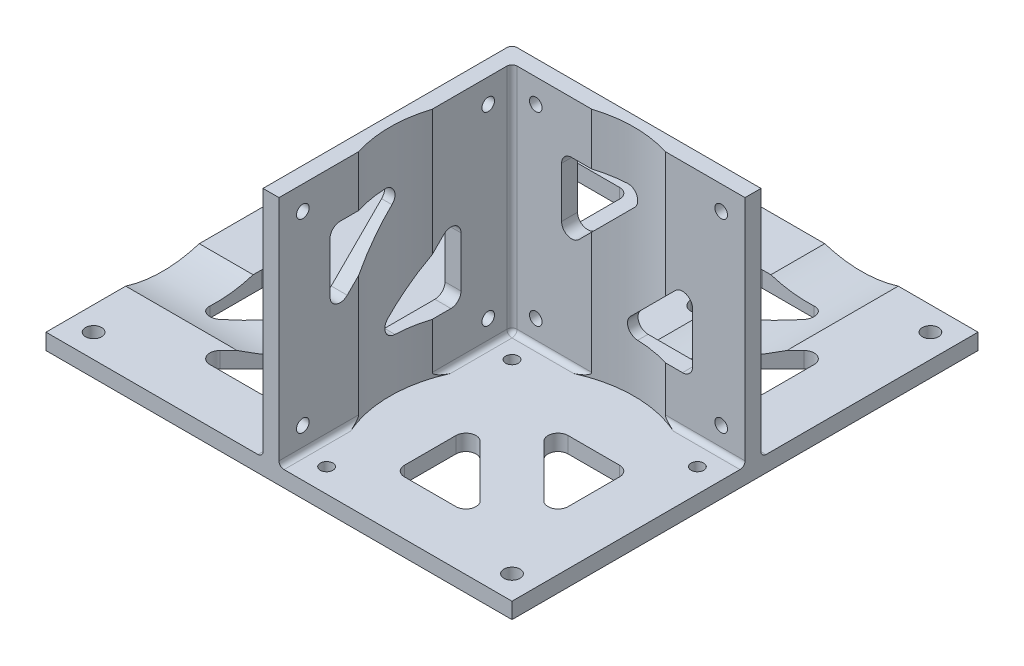
SolidWorks part; units mm, degrees
ref_plane "Front Plane" through (0, 0, 0) normal (0, 0, 1) x (1, 0, 0)
ref_plane "Top Plane" through (0, 0, 0) normal (0, 1, 0) x (1, 0, 0)
ref_plane "Right Plane" through (0, 0, 0) normal (1, 0, 0) x (0, 0, -1)
sketch "Sketch1" plane through (0, 0, 0) normal (0, 1, 0) x (1, 0, 0)
  line L0 (-41.525, 46.25) -> (-41.525, -46.25) construction
  line L1 (-46.25, -46.25) -> (46.25, -46.25)
  line L2 (-46.25, -46.25) -> (-46.25, 46.25)
  line L3 (-46.25, 46.25) -> (46.25, 46.25)
  line L4 (46.25, -46.25) -> (46.25, 46.25)
  line L5 (-46.25, -46.25) -> (46.25, 46.25) construction
  line L6 (-46.25, 46.25) -> (46.25, -46.25) construction
  line L7 (-46.25, -41.525) -> (46.25, -41.525) construction
  line L8 (41.525, -46.25) -> (41.525, 46.25) construction
  line L9 (-46.25, 41.525) -> (46.25, 41.525) construction
  circle A0 centre (-41.525, -41.525) radius 1.6
  circle A1 centre (-41.525, 41.525) radius 1.6
  circle A2 centre (41.525, 41.525) radius 1.6
  circle A3 centre (41.525, -41.525) radius 1.6
  point P0 (0, 0)
  dimension "D7" = 3.2
  dimension "D8" = 3.2
  dimension "D9" = 3.2
  dimension "D10" = 3.2
  dimension "D1" = 92.5
  dimension "D2" = 92.5
  dimension "D3" = 4.725
  dimension "D4" = 4.725
  dimension "D5" = 4.725
  dimension "D6" = 4.725
extrude "Base Plate" add sketch "Sketch1" along normal blind 3.175
sketch "Sketch2" plane through (0, 3.175, 0) normal (0, 1, 0) x (1, 0, 0)
  line L0 (0, 0) -> (46.25, 0)
  line L1 (46.25, -46.25) -> (46.25, 46.25) construction
  line L2 (0, 0) -> (0, -46.25)
  line L3 (-46.25, -46.25) -> (46.25, -46.25) construction
  line L4 (-3.175, -46.25) -> (-3.175, 3.175)
  line L7 (-3.175, 3.175) -> (46.25, 3.175)
  line L8 (-3.175, -46.25) -> (0, -46.25)
  line L9 (46.25, 0) -> (46.25, 3.175)
  dimension "D1" = 46.25
  dimension "D2" = 3.175
  dimension "D3" = 3.175
extrude "L-Bracket" add sketch "Sketch2" along normal blind 46.25
sketch "Sketch3" plane through (0, 3.175, 0) normal (0, 1, 0) x (1, 0, 0)
  line L0 (0, 0) -> (46.25, -46.25) construction
  line L1 (0, -46.25) -> (46.25, 0) construction
  line L5 (0, -46.25) -> (0, 0) construction
  circle A0 centre (23.125, -23.125) radius 21.625 construction
  circle A2 centre (41.525, -4.725) radius 0.2
  circle A3 centre (4.725, -4.725) radius 0.2
  circle A4 centre (4.725, -41.525) radius 0.2
  dimension "D1" = 43.25
  dimension "D4" = 4.725
extrude "RW Holes" cut sketch "Sketch3" against normal through all
sketch "Sketch7" plane through (0, 0, 0) normal (0, 0, 1) x (1, 0, 0)
  line L0 (0, 3.175) -> (46.25, 49.425) construction
  line L1 (0, 49.425) -> (46.25, 3.175) construction
  line L2 (46.25, 49.425) -> (46.25, 3.175) construction
  line L3 (0, 3.175) -> (46.25, 3.175) construction
  circle A0 centre (23.125, 26.3) radius 21.625 construction
  circle A1 centre (41.525, 7.9) radius 0.2
  circle A2 centre (4.725, 7.9) radius 0.2
  circle A3 centre (4.725, 44.7) radius 0.2
  circle A4 centre (41.525, 44.7) radius 0.2
  dimension "D1" = 43.25
  dimension "D2" = 0.4
  dimension "D3" = 4
  dimension "D4" = 4.725
  dimension "D5" = 41.525
  dimension "D6" = 4.725
  dimension "D8" = 46.25
extrude "RW Holes 2" cut sketch "Sketch7" against normal through all
sketch "Sketch8" plane through (0, 0, 0) normal (1, 0, 0) x (0, 0, -1)
  line L0 (-46.25, 49.425) -> (0, 3.175) construction
  line L1 (-46.25, 3.175) -> (0, 49.425) construction
  line L2 (-46.25, 3.175) -> (0, 3.175) construction
  circle A0 centre (-23.125, 26.3) radius 21.625 construction
  circle A1 centre (-41.525, 7.9) radius 0.2
  circle A2 centre (-41.525, 44.7) radius 0.2
  circle A3 centre (-4.725, 44.7) radius 0.2
  circle A4 centre (-4.725, 7.9) radius 0.2
  dimension "D1" = 43.25
  dimension "D4" = 0.4
  dimension "D2" = 4
  dimension "D3" = 4.725
  dimension "D5" = 41.525
  dimension "D6" = 4.725
extrude "RW Holes 3" cut sketch "Sketch8" against normal blind 45
sketch "Sketch10" plane through (0, 0, 0) normal (0, -1, 0) x (1, 0, 0)
  line L0 (-46.25, 46.25) -> (46.25, -46.25) construction
  line L1 (21.9291, 15.6133) -> (32.1447, 25.8289)
  line L2 (-46.25, -46.25) -> (46.25, 46.25) construction
  line L3 (35.559, 24.4147) -> (35.559, 14.1991)
  line L4 (33.559, 12.1991) -> (23.3433, 12.1991)
  line L5 (46.25, 46.25) -> (46.25, -46.25) construction
  line L6 (24.4147, 35.559) -> (14.1991, 35.559)
  line L7 (15.6133, 21.9291) -> (25.8289, 32.1447)
  line L8 (12.1991, 33.559) -> (12.1991, 23.3433)
  line L9 (35.559, -24.4147) -> (35.559, -14.1991)
  line L10 (33.559, -12.1991) -> (23.3433, -12.1991)
  line L11 (21.9291, -15.6133) -> (32.1447, -25.8289)
  line L12 (12.1991, -33.559) -> (12.1991, -23.3433)
  line L13 (15.6133, -21.9291) -> (25.8289, -32.1447)
  line L14 (24.4147, -35.559) -> (14.1991, -35.559)
  line L15 (-24.4147, -35.559) -> (-14.1991, -35.559)
  line L16 (-12.1991, -33.559) -> (-12.1991, -23.3433)
  line L17 (-15.6133, -21.9291) -> (-25.8289, -32.1447)
  line L18 (-33.559, -12.1991) -> (-23.3433, -12.1991)
  line L19 (-21.9291, -15.6133) -> (-32.1447, -25.8289)
  line L20 (-35.559, -24.4147) -> (-35.559, -14.1991)
  line L21 (-35.559, 24.4147) -> (-35.559, 14.1991)
  line L22 (-33.559, 12.1991) -> (-23.3433, 12.1991)
  line L23 (-21.9291, 15.6133) -> (-32.1447, 25.8289)
  line L24 (-12.1991, 33.559) -> (-12.1991, 23.3433)
  line L25 (-15.6133, 21.9291) -> (-25.8289, 32.1447)
  line L26 (-24.4147, 35.559) -> (-14.1991, 35.559)
  arc A0 (35.559, 14.1991) -> (33.559, 12.1991) centre (33.559, 14.1991) cw
  arc A1 (32.1447, 25.8289) -> (35.559, 24.4147) centre (33.559, 24.4147) cw
  arc A2 (21.9291, 15.6133) -> (23.3433, 12.1991) centre (23.3433, 14.1991) ccw
  arc A3 (25.8289, 32.1447) -> (24.4147, 35.559) centre (24.4147, 33.559) ccw
  arc A4 (14.1991, 35.559) -> (12.1991, 33.559) centre (14.1991, 33.559) ccw
  arc A5 (15.6133, 21.9291) -> (12.1991, 23.3433) centre (14.1991, 23.3433) cw
  arc A6 (35.559, -14.1991) -> (33.559, -12.1991) centre (33.559, -14.1991) ccw
  arc A7 (21.9291, -15.6133) -> (23.3433, -12.1991) centre (23.3433, -14.1991) cw
  arc A8 (32.1447, -25.8289) -> (35.559, -24.4147) centre (33.559, -24.4147) ccw
  arc A9 (15.6133, -21.9291) -> (12.1991, -23.3433) centre (14.1991, -23.3433) ccw
  arc A10 (14.1991, -35.559) -> (12.1991, -33.559) centre (14.1991, -33.559) cw
  arc A11 (25.8289, -32.1447) -> (24.4147, -35.559) centre (24.4147, -33.559) cw
  arc A12 (-14.1991, -35.559) -> (-12.1991, -33.559) centre (-14.1991, -33.559) ccw
  arc A13 (-15.6133, -21.9291) -> (-12.1991, -23.3433) centre (-14.1991, -23.3433) cw
  arc A14 (-25.8289, -32.1447) -> (-24.4147, -35.559) centre (-24.4147, -33.559) ccw
  arc A15 (-21.9291, -15.6133) -> (-23.3433, -12.1991) centre (-23.3433, -14.1991) ccw
  arc A16 (-35.559, -14.1991) -> (-33.559, -12.1991) centre (-33.559, -14.1991) cw
  arc A17 (-32.1447, -25.8289) -> (-35.559, -24.4147) centre (-33.559, -24.4147) cw
  arc A18 (-35.559, 14.1991) -> (-33.559, 12.1991) centre (-33.559, 14.1991) ccw
  arc A19 (-21.9291, 15.6133) -> (-23.3433, 12.1991) centre (-23.3433, 14.1991) cw
  arc A20 (-32.1447, 25.8289) -> (-35.559, 24.4147) centre (-33.559, 24.4147) ccw
  arc A21 (-15.6133, 21.9291) -> (-12.1991, 23.3433) centre (-14.1991, 23.3433) ccw
  arc A22 (-14.1991, 35.559) -> (-12.1991, 33.559) centre (-14.1991, 33.559) cw
  arc A23 (-25.8289, 32.1447) -> (-24.4147, 35.559) centre (-24.4147, 33.559) cw
  point P18 (35.559, 29.2431)
  point P21 (18.5149, 12.1991)
  dimension "D4" = 2
  dimension "D1" = 10.691
  dimension "D2" = 27.7351
  dimension "D3" = 17.0069
  dimension "D6" = 10.691
  dimension "D7" = 58.4491
  dimension "D5" = 4
extrude "WR1" cut sketch "Sketch10" against normal blind 45
sketch "Sketch11" plane through (0, 0, 0) normal (1, 0, 0) x (0, 0, -1)
  line L0 (-46.25, 49.425) -> (0, 3.175) construction
  line L1 (-46.25, 3.175) -> (0, 49.425) construction
  line L2 (-36.1242, 37.2992) -> (-36.1242, 27.2939)
  line L3 (-32.71, 25.8797) -> (-22.7047, 35.885)
  line L4 (-34.1242, 39.2992) -> (-24.1189, 39.2992)
  line L5 (-10.1258, 15.3008) -> (-10.1258, 25.3061)
  line L6 (-23.5453, 16.715) -> (-13.54, 26.7203)
  line L7 (-12.1258, 13.3008) -> (-22.1311, 13.3008)
  circle A0 centre (-4.725, 44.7) radius 0.2 construction
  arc A1 (-22.7047, 35.885) -> (-24.1189, 39.2992) centre (-24.1189, 37.2992) ccw
  arc A2 (-36.1242, 37.2992) -> (-34.1242, 39.2992) centre (-34.1242, 37.2992) cw
  arc A3 (-36.1242, 27.2939) -> (-32.71, 25.8797) centre (-34.1242, 27.2939) ccw
  arc A4 (-13.54, 26.7203) -> (-10.1258, 25.3061) centre (-12.1258, 25.3061) cw
  arc A5 (-12.1258, 13.3008) -> (-10.1258, 15.3008) centre (-12.1258, 15.3008) ccw
  arc A6 (-22.1311, 13.3008) -> (-23.5453, 16.715) centre (-22.1311, 15.3008) cw
  point P19 (-19.2905, 39.2992)
  point P22 (-36.1242, 39.2992)
  point P25 (-36.1242, 22.4655)
  dimension "D3" = 2
  dimension "D1" = 16.8337
  dimension "D2" = 14.5655
extrude "WR2" cut sketch "Sketch11" against normal blind 10
sketch "Sketch12" plane through (0, 0, 0) normal (0, 0, 1) x (1, 0, 0)
  line L0 (-0.2859, 49.2555) -> (45.9641, 3.0055) construction
  line L1 (-0.2859, 3.0055) -> (45.9641, 49.2555) construction
  line L2 (9.8399, 37.1297) -> (9.8399, 27.1244)
  line L3 (13.2541, 25.7102) -> (23.2594, 35.7154)
  line L4 (11.8399, 39.1297) -> (21.8451, 39.1297)
  line L5 (35.8382, 15.1313) -> (35.8382, 25.1365)
  line L6 (22.4188, 16.5455) -> (32.424, 26.5508)
  line L7 (33.8382, 13.1313) -> (23.833, 13.1313)
  arc A1 (23.2594, 35.7154) -> (21.8451, 39.1297) centre (21.8451, 37.1297) ccw
  arc A2 (9.8399, 37.1297) -> (11.8399, 39.1297) centre (11.8399, 37.1297) cw
  arc A3 (9.8399, 27.1244) -> (13.2541, 25.7102) centre (11.8399, 27.1244) ccw
  arc A4 (32.424, 26.5508) -> (35.8382, 25.1365) centre (33.8382, 25.1365) cw
  arc A5 (33.8382, 13.1313) -> (35.8382, 15.1313) centre (33.8382, 15.1313) ccw
  arc A6 (23.833, 13.1313) -> (22.4188, 16.5455) centre (23.833, 15.1313) cw
  circle A7 centre (4.725, 44.7) radius 0.2 construction
  point P19 (26.6736, 39.1297)
  point P22 (9.8399, 39.1297)
  point P25 (9.8399, 22.296)
  dimension "D3" = 2
  dimension "D1" = 16.8337
  dimension "D2" = 5.1149
  dimension "D4" = 17.6938
  dimension "D5" = 41.2391
  dimension "D6" = 4.5555
extrude "WR3" cut sketch "Sketch12" against normal blind 10
fillet "Fillet1" radius 1 6 edges at (0, 26.3, 0) (23.125, 3.175, 0) (0, 3.175, 23.125) (-3.175, 26.3, -3.175) (21.5375, 3.175, -3.175) (-3.175, 3.175, 21.5375)
hole_wizard "Tap Drill for M3x0.5 Tap1" positions "3DSketch2" profile "Sketch14" hole size "M3x0.5" standard "ANSI Metric" end condition through all
sketch3d "3DSketch2"
  line L0 (41.525, 0, 4.725) -> (41.525, 3.175, 4.725) construction
  line L1 (4.725, 0, 4.725) -> (4.725, 3.175, 4.725) construction
  line L2 (4.725, 0, 41.525) -> (4.725, 3.175, 41.525) construction
  point P0 (41.525, 3.175, 4.725)
  point P4 (4.725, 3.175, 4.725)
  point P8 (4.725, 3.175, 41.525)
sketch "Sketch14" plane through (41.525, 3.175, 4.725) normal (1, 0, 0) x (0, 0, 1)
  line L0 (0, 0) -> (0, 3.175)
  line L1 (0, 3.175) -> (1.25, 3.175)
  line L2 (1.25, 3.175) -> (1.25, 0)
  line L5 (1.25, 0) -> (0, 0)
  line L11 (0, -6.35) -> (0, 107.95) construction
  dimension "Thru Hole Dia." = 2.5
  dimension "Thru Hole Depth" = 3.175
hole_wizard "Tap Drill for M3x0.5 Tap2" positions "3DSketch3" profile "Sketch15" hole size "M3x0.5" standard "ANSI Metric" end condition through all
sketch3d "3DSketch3"
  line L0 (41.525, 44.7, -3.175) -> (41.525, 44.7, 0) construction
  line L1 (41.525, 7.9, -3.175) -> (41.525, 7.9, 0) construction
  line L2 (4.725, 7.9, -3.175) -> (4.725, 7.9, 0) construction
  line L3 (4.725, 44.7, -3.175) -> (4.725, 44.7, 0) construction
  point P0 (41.525, 44.7, 0)
  point P4 (41.525, 7.9, 0)
  point P8 (4.725, 7.9, 0)
  point P12 (4.725, 44.7, 0)
sketch "Sketch15" plane through (41.525, 44.7, 0) normal (1, 0, 0) x (0, -1, 0)
  line L0 (0, 0) -> (0, 46.25)
  line L1 (0, 46.25) -> (1.25, 46.25)
  line L2 (1.25, 46.25) -> (1.25, 0)
  line L5 (1.25, 0) -> (0, 0)
  line L11 (0, -6.35) -> (0, 107.95) construction
  dimension "Thru Hole Dia." = 2.5
  dimension "Thru Hole Depth" = 46.25
hole_wizard "Tap Drill for M3x0.5 Tap3" positions "3DSketch4" profile "Sketch16" hole size "M3x0.5" standard "ANSI Metric" end condition through all
sketch3d "3DSketch4"
  line L0 (-3.175, 44.7, 4.725) -> (0, 44.7, 4.725) construction
  line L1 (-3.175, 44.7, 41.525) -> (0, 44.7, 41.525) construction
  line L2 (-3.175, 7.9, 41.525) -> (0, 7.9, 41.525) construction
  line L3 (-3.175, 7.9, 4.725) -> (0, 7.9, 4.725) construction
  point P0 (-3.175, 44.7, 4.725)
  point P4 (-3.175, 44.7, 41.525)
  point P8 (-3.175, 7.9, 41.525)
  point P12 (-3.175, 7.9, 4.725)
sketch "Sketch16" plane through (-3.175, 44.7, 4.725) normal (0, 1, 0) x (0, 0, 1)
  line L0 (0, 0) -> (0, 49.425)
  line L1 (0, 49.425) -> (1.25, 49.425)
  line L2 (1.25, 49.425) -> (1.25, 0)
  line L5 (1.25, 0) -> (0, 0)
  line L11 (0, -6.35) -> (0, 107.95) construction
  dimension "Thru Hole Dia." = 2.5
  dimension "Thru Hole Depth" = 49.425
sketch "Sketch18" plane through (0, 49.425, 0) normal (0, 1, 0) x (1, 0, 0)
  line L0 (41.525, -41.525) -> (4.725, -4.725) construction
  line L1 (41.525, -4.725) -> (4.725, -41.525) construction
  circle A0 centre (23.125, -23.125) radius 24.25
extrude "Cut-Extrude1" cut sketch "Sketch18" against normal up to surface (46.25 mm away) up to face at (41.525, 3.175, 5.975)
sketch "Sketch19" plane through (0, 0, -46.25) normal (0, 0, -1) x (-1, 0, 0)
  line L0 (-41.525, 44.7) -> (-4.725, 7.9) construction
  line L1 (-4.725, 44.7) -> (-41.525, 7.9) construction
  circle A0 centre (-23.125, 26.3) radius 24.25
extrude "Cut-Extrude2" cut sketch "Sketch19" against normal up to surface (43.075 mm away) contours A0 up to face at (42.775, 44.7, -3.175)
sketch "Sketch20" plane through (-46.25, 0, 0) normal (-1, 0, 0) x (0, 0, 1)
  line L0 (4.725, 44.7) -> (41.525, 7.9) construction
  line L1 (41.525, 44.7) -> (4.725, 7.9) construction
  circle A0 centre (23.125, 26.3) radius 24.25
extrude "Cut-Extrude3" cut sketch "Sketch20" against normal up to surface (43.075 mm away) up to face at (-3.175, 44.7, 5.975)
